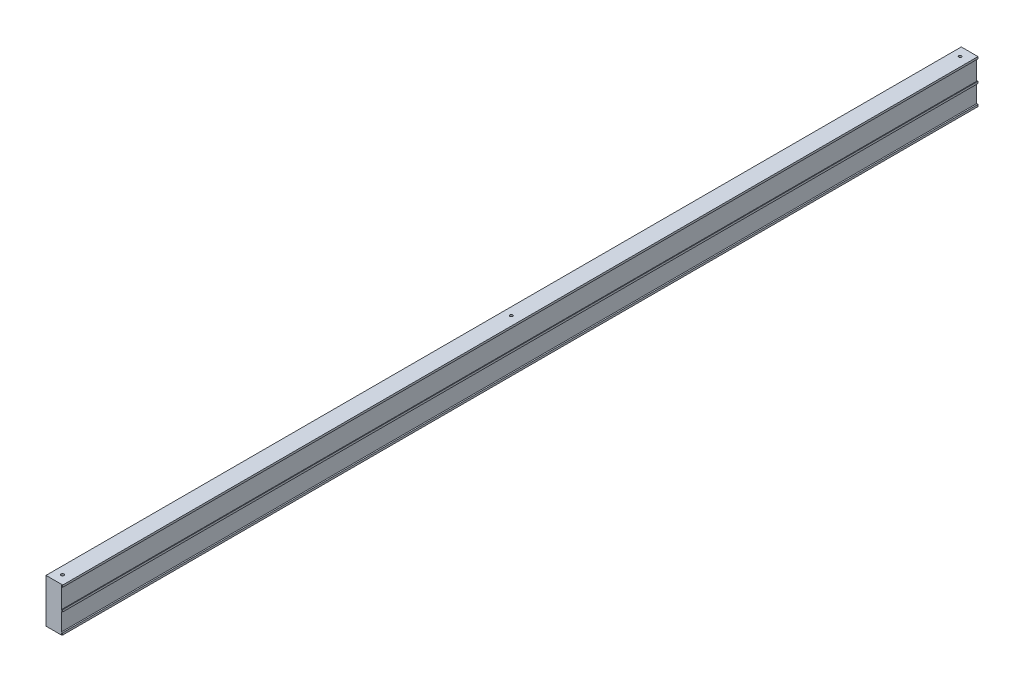
SolidWorks part; units mm, degrees
ref_plane "Alzado" through (0, 0, 0) normal (0, 0, 1) x (1, 0, 0)
ref_plane "Planta" through (0, 0, 0) normal (0, 1, 0) x (1, 0, 0)
ref_plane "Vista lateral" through (0, 0, 0) normal (1, 0, 0) x (0, 0, -1)
sketch "Croquis1" plane through (0, 0, 0) normal (0, 0, 1) x (1, 0, 0)
  line L0 (17.5, 50) -> (20.5, 50)
  line L1 (-17.5, -50) -> (17.5, -50)
  line L2 (-17.5, -50) -> (-17.5, 50)
  line L3 (-17.5, 50) -> (17.5, 50)
  line L4 (17.5, -50) -> (17.5, -45.5)
  line L5 (-17.5, -50) -> (17.5, 50) construction
  line L6 (-17.5, 50) -> (17.5, -50) construction
  line L7 (20.5, 50) -> (20.5, 45.5)
  line L8 (20.5, 45.5) -> (19, 45.5)
  line L9 (19, 45.5) -> (19, 48.5)
  line L10 (19, 48.5) -> (17.5, 48.5)
  line L11 (17.5, -44) -> (20.5, -44)
  line L12 (20.5, -44) -> (20.5, -48.5)
  line L13 (20.5, -48.5) -> (19, -48.5)
  line L14 (19, -48.5) -> (19, -45.5)
  line L15 (19, -45.5) -> (17.5, -45.5)
  line L16 (17.5, -3) -> (20.5, -3)
  line L17 (20.5, -3) -> (20.5, 1.5)
  line L18 (20.5, 1.5) -> (19, 1.5)
  line L19 (19, 1.5) -> (19, -1.5)
  line L20 (19, -1.5) -> (17.5, -1.5)
  line L21 (17.5, -1.5) -> (17.5, 48.5)
  line L22 (17.5, -44) -> (17.5, -3)
  point P0 (0, 0)
  point P20 (18.25, -45.5)
  dimension "D1" = 35
  dimension "D2" = 100
  dimension "D3" = 1.5
  dimension "D4" = 3
  dimension "D5" = 1.5
  dimension "D6" = 3
  dimension "D7" = 3
  dimension "D8" = 1.5
  dimension "D9" = 1.5
  dimension "D10" = 1.5
  dimension "D11" = 3
  dimension "D12" = 1.5
  dimension "D13" = 1.5
  dimension "D14" = 3
  dimension "D15" = 1.5
  dimension "D16" = 3
extrude "Saliente-Extruir1" add sketch "Croquis1" along normal blind 2080
sketch "Croquis2" plane through (0, 50, 0) normal (0, 1, 0) x (1, 0, 0)
  line L0 (-17.5, -2080) -> (-17.5, 0) construction
  line L1 (20.5, 0) -> (-17.5, 0) construction
  line L2 (20.5, -2080) -> (-17.5, -2080) construction
  circle A0 centre (0, -20) radius 3.175
  circle A1 centre (0, -1040) radius 3.175
  circle A2 centre (0, -2060) radius 3.175
  dimension "D2" = 6.35
  dimension "D6" = 6.35
  dimension "D7" = 6.35
  dimension "D1" = 17.5
  dimension "D3" = 20
  dimension "D4" = 20
  dimension "D5" = 1040
extrude "Cortar-Extruir1" cut sketch "Croquis2" against normal blind 30
